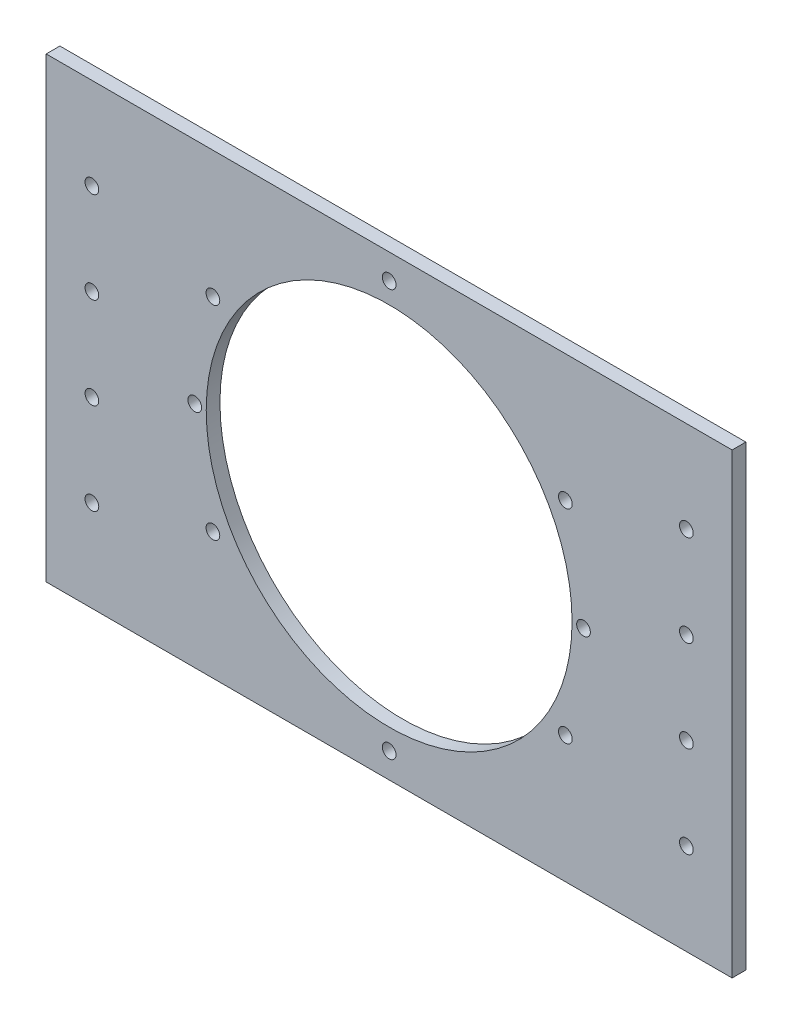
SolidWorks part; units mm, degrees
ref_plane "前视基准面" through (0, 0, 0) normal (0, 0, 1) x (1, 0, 0)
ref_plane "上视基准面" through (0, 0, 0) normal (0, 1, 0) x (1, 0, 0)
ref_plane "右视基准面" through (0, 0, 0) normal (1, 0, 0) x (0, 0, -1)
other "Configuration Table"
sketch "草图1" plane through (0, 0, 0) normal (0, 0, 1) x (1, 0, 0)
  line L0 (-65, 50) -> (-65, -50) construction
  line L1 (-75, 50) -> (75, 50)
  line L2 (-75, 50) -> (-75, -50)
  line L3 (-75, -50) -> (75, -50)
  line L4 (75, 50) -> (75, -50)
  line L5 (-75, 50) -> (75, -50) construction
  line L6 (-75, -50) -> (75, 50) construction
  line L7 (0, 0) -> (0, 106.8421) construction
  circle A0 centre (-65, 30) radius 1.5
  circle A1 centre (-65, 10) radius 1.5
  circle A2 centre (-65, -10) radius 1.5
  circle A3 centre (-65, -30) radius 1.5
  circle A4 centre (65, -30) radius 1.5
  circle A5 centre (65, -10) radius 1.5
  circle A6 centre (65, 10) radius 1.5
  circle A7 centre (65, 30) radius 1.5
  circle A8 centre (0, 0) radius 40
  circle A9 centre (0, 0) radius 44.5 construction
  circle A10 centre (0, 0) radius 42.5 construction
  circle A11 centre (42.5, 0) radius 1.5
  circle A12 centre (-42.5, 0) radius 1.5
  circle A13 centre (0, 44.5) radius 1.5
  circle A14 centre (0, 0) radius 40
  circle A16 centre (0, 0) radius 40
  circle A18 centre (0, 0) radius 40
  circle A20 centre (-44.5, 0) radius 1.5 [skipped]
  circle A21 centre (0, -44.5) radius 1.5 [skipped]
  circle A22 centre (44.5, 0) radius 1.5 [skipped]
  circle A23 centre (38.5381, 22.25) radius 1.5
  circle A24 centre (38.5381, -22.25) radius 1.5
  circle A25 centre (0, -44.5) radius 1.5
  circle A26 centre (-38.5381, -22.25) radius 1.5
  circle A27 centre (-38.5381, 22.25) radius 1.5
  point P0 (0, 0)
  point P47 (0, 0)
  point P57 (0, 0)
  dimension "D8" = 3
  dimension "D9" = 3
  dimension "D10" = 3
  dimension "D11" = 3
  dimension "D12" = 80
  dimension "D13" = 89
  dimension "D14" = 85
  dimension "D15" = 3
  dimension "D16" = 3
  dimension "D17" = 3
  dimension "D1" = 100
  dimension "D2" = 150
  dimension "D3" = 10
  dimension "D4" = 20
  dimension "D5" = 20
  dimension "D6" = 20
  dimension "D7" = 20
  dimension "D18" = 4
  dimension "D19" = 6
extrude "凸台-拉伸2" add sketch "草图1" along normal blind 3 contours L4 L1 L2 L3 A27 A26 A25 A24 A23 A13 A12 A11 A8 A6 A4 A3 A2 A1 A0 A5 A7
